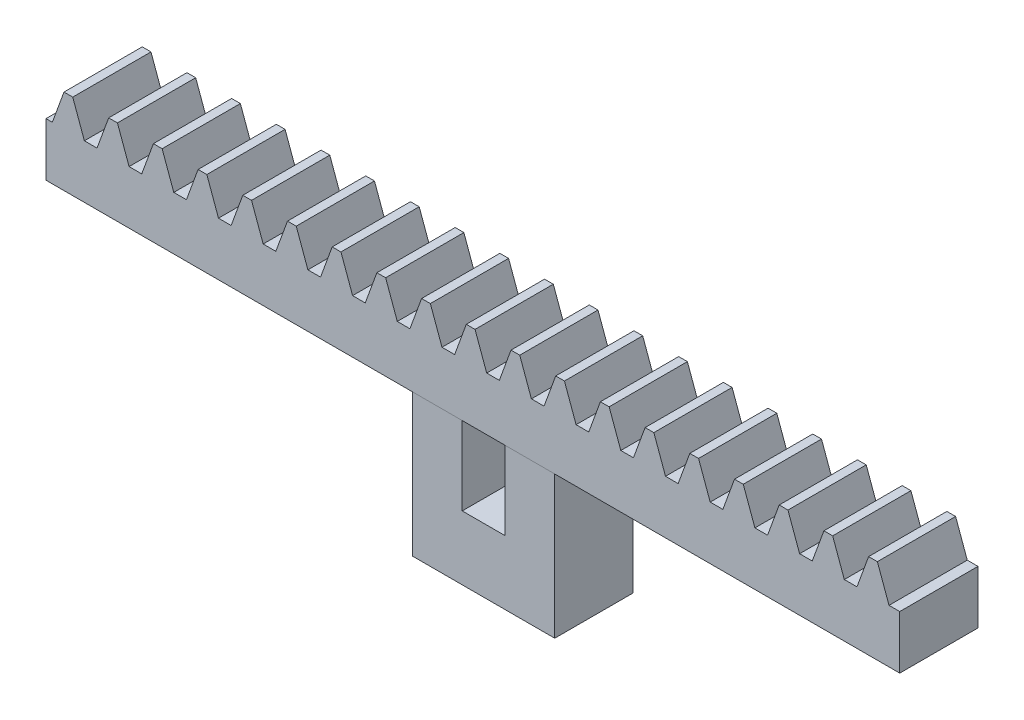
SolidWorks part; units mm, degrees
extrude "Blank" add sketch "BlankSke" against normal blind 5.5
sketch "BlankSke" plane through (0, 0, 0) normal (0, 0, 1) x (1, 0, 0)
  line L1 (0, 0) -> (60, 0)
  line L2 (0, 0) -> (0, 6)
  line L3 (0, 6) -> (60, 6)
  line L4 (60, 0) -> (60, 6)
  dimension "Length" = 60
  dimension "Blank_height" = 6
ref_plane "Plane1" through (0, 0, 0) normal (0, 0, 1) x (1, 0, 0)
ref_plane "Plane2" through (0, 0, 0) normal (0, 1, 0) x (1, 0, 0)
ref_plane "Plane3" through (0, 0, 0) normal (1, 0, 0) x (0, 0, -1)
sketch "HoldingSke" plane through (0, 0, 0) normal (0, 1, 0) x (1, 0, 0)
  line L0 (0, 0) -> (0.1392, 0.9903)
  line L1 (-15, 0) -> (100, 0) construction
  line L2 (0, 0) -> (-2.1039, 2.3779)
  line L3 (0, 0) -> (-11.863, 4.5341)
  line L4 (0, 0) -> (8.0624, 3.0949)
  line L5 (0, 0) -> (-23.7986, -8.8762)
  line L6 (0, 0) -> (-10.5278, -7.1032)
  line L9 (-71.009, 38.7566) -> (-14.6274, 59.2778)
  line L10 (-76.2, 3.3779) -> (-71.2, 3.3779)
  line L11 (0, 0) -> (-5.5, 0)
  line L12 (-76.2, 101.6) -> (-76.162, 101.6)
  line L13 (24.9733, 27.94) -> (52.9518, 28.4284)
  line L14 (24.9733, 27.94) -> (24.9743, 27.94)
  line L15 (24.9733, 27.94) -> (100.4006, 29.5858)
  circle A0 centre (0, 0) radius 19.05
  circle A1 centre (0, 0) radius 2.5
  circle A2 centre (0, 0) radius 12.7
  dimension "MPH" = 5
  dimension "Diameter" = 38.1
  dimension "Num_teeth" = 21
  dimension "Pitch" = 1
  dimension "Show_teeth" = 998
  dimension "Thickness" = 12.7
  dimension "Ap" = 20
  dimension "Pitch_height" = 5
  dimension "Width" = 5.5
  dimension "Backlash" = 0.038
  dimension "Addendum_fac" = 1
  dimension "Dedendum_fac" = 1.25
  dimension "Clearance_fac" = 0.25
  dimension "Dedendum_add" = 0.001
  dimension "Length" = 60
  dimension "Module" = 1
sketch "TooCutSkeIll" plane through (0, 0, 0) normal (0, 0, 1) x (1, 0, 0)
  line L0 (-1.2538, 5.9737) -> (-0.5045, 3.9152)
  line L1 (-0.2687, 3.75) -> (0.2687, 3.75)
  line L2 (0.5045, 3.9152) -> (1.2538, 5.9737)
  line L3 (60, 6) -> (0, 6) construction
  line L4 (0, 0) -> (0, 64.897) construction
  line L5 (-13.208, 5) -> (12.954, 5) construction
  line L6 (0, 0) -> (60, 0) construction
  line L7 (0.8994, 5) -> (0.8994, 48.7463) construction
  line L8 (-0.8994, 5) -> (-0.8994, 48.7463) construction
  line L9 (1.2914, 6) -> (1.2914, 6.0254)
  line L10 (-1.2914, 6) -> (-1.2914, 6.0254)
  line L11 (-1.2914, 6.0254) -> (1.2914, 6.0254)
  arc A0 (0.2687, 3.75) -> (0.5045, 3.9152) centre (0.2687, 4.001) ccw
  arc A1 (-0.5045, 3.9152) -> (-0.2687, 3.75) centre (-0.2687, 4.001) ccw
  arc A2 (1.2914, 6) -> (1.2538, 5.9737) centre (1.2914, 5.96) ccw
  arc A3 (-1.2538, 5.9737) -> (-1.2914, 6) centre (-1.2914, 5.96) ccw
  dimension "Pitch_height" = 5
  dimension "Addendum_plus" = 1.0254
  dimension "Pressure_angle" = 20
  dimension "Gap_width" = 1.7988
  dimension "Dedendum" = 1.25
extrude "ToothCutIll" [suppressed] cut sketch "TooCutSkeIll" against normal through all
sketch "TooCutSkeSim" plane through (0, 0, 0) normal (0, 0, 1) x (1, 0, 0)
  line L0 (0.4444, 3.75) -> (-0.4444, 3.75)
  line L1 (1.2726, 6.0254) -> (0.4444, 3.75)
  line L2 (0, 17.4625) -> (0, 53.467) construction
  line L3 (1.2726, 6.0254) -> (-1.2726, 6.0254)
  line L6 (-1.2726, 6.0254) -> (-0.4444, 3.75)
  line L9 (-0.8994, 5) -> (0.8994, 5) construction
  line L10 (0, 0) -> (60, 0) construction
  line L11 (0.8994, 5) -> (0.8994, 53.467) construction
  line L12 (-0.8994, 5) -> (-0.8994, 53.467) construction
  dimension "Pitch_height" = 5
  dimension "Addendum_plus" = 1.0254
  dimension "Pressure_angle" = 20
  dimension "Gap_width" = 1.7988
  dimension "Dedendum" = 1.25
extrude "ToothCutSim" cut sketch "TooCutSkeSim" against normal through all
pattern_linear "TeethCuts" count 20 spacing 3.1416 along (1, 0, 0) of "ToothCutIll", "ToothCutSim"
sketch "ｽｹｯﾁ1" plane through (0, 0, 0) normal (0, 0, 1) x (1, 0, 0)
  line L0 (0, 0) -> (60, 0) construction
  line L1 (35.7525, -10) -> (25.7525, -10)
  line L2 (35.7525, -10) -> (35.7525, 0)
  line L3 (35.7525, 0) -> (25.7525, 0)
  line L4 (25.7525, -10) -> (25.7525, 0)
  line L5 (35.7525, -10) -> (25.7525, 0) construction
  line L6 (35.7525, 0) -> (25.7525, -10) construction
  point P0 (30.7525, -5)
  dimension "D1" = 10
  dimension "D2" = 10
extrude "ﾎﾞｽ - 押し出し1" add sketch "ｽｹｯﾁ1" against normal blind 5.5 separate body
sketch "ｽｹｯﾁ2" plane through (0, 0, 0) normal (0, 0, 1) x (1, 0, 0)
  line L0 (35.7525, 0) -> (25.7525, 0) construction
  line L1 (32.2525, 0) -> (29.2525, 0)
  line L2 (32.2525, 0) -> (32.2525, -5.5)
  line L3 (32.2525, -5.5) -> (29.2525, -5.5)
  line L4 (29.2525, 0) -> (29.2525, -5.5)
  line L5 (32.2525, 0) -> (29.2525, -5.5) construction
  line L6 (32.2525, -5.5) -> (29.2525, 0) construction
  line L8 (35.7525, -10) -> (35.7525, 0) construction
  point P0 (30.7525, -2.75)
  dimension "D1" = 3
  dimension "D2" = 5.5
  dimension "D3" = 5
extrude "ｶｯﾄ - 押し出し1" cut sketch "ｽｹｯﾁ2" against normal through all
equation "' \"Module@HoldingSke\" = 6.35"
equation "' \"Num_teeth@HoldingSke\" = 12"
equation "' \"Ap@HoldingSke\" =  20"
equation "' \"Ap@HoldingSke\" = 20"
equation "' \"Width@HoldingSke\" = 0.25 * 25.4"
equation "' \"Show_teeth@HoldingSke\" = 500"
equation "' \"Backlash@HoldingSke\" = 0.009 * 25.4"
equation "' \"Addendum_fac@HoldingSke\" = 1.0"
equation "' \"Dedendum_fac@HoldingSke\" = 1.25"
equation "' \"Dedendum_add@HoldingSke\" = 0.00005 * 25.4"
equation "' \"Clearance_fac@HoldingSke\" = 0.25"
equation "' \"Pitch_height@HoldingSke\" = 1 * 25.4"
equation "' \"Length@HoldingSke\" = 4.71 * 25.4"
equation "\"Pitch@HoldingSke\" = 1 / \"Module@HoldingSke\""
equation "\"MPH@HoldingSke\" = \"Dedendum_fac@HoldingSke\" / \"Pitch@HoldingSke\" + 2 * \"Dedendum_add@HoldingSke\" + 0.002 * 25.4"
equation "\"MPH@HoldingSke\" = ((sgn( \"MPH@HoldingSke\" - \"Pitch_height@HoldingSke\")+1)*( \"MPH@HoldingSke\" - \"Pitch_height@HoldingSke\"))/2 + \"Pitch_height@HoldingSke\""
equation "\"Blank_height@BlankSke\" = \"Pitch_height@HoldingSke\" + \"Addendum_fac@HoldingSke\"  / \"Pitch@HoldingSke\" "
equation "\"Length@BlankSke\" =  \"Length@HoldingSke\""
equation "\"Face_width@Blank\" = \"Width@HoldingSke\""
equation "\"Pressure_angle@TooCutSkeIll\" = \"Ap@HoldingSke\""
equation "\"Addendum_plus@TooCutSkeIll\" =  \"Addendum_fac@HoldingSke\"  / \"Pitch@HoldingSke\" + 0.001 *25.4"
equation "\"Dedendum@TooCutSkeIll\" = \"Dedendum_fac@HoldingSke\"  / \"Pitch@HoldingSke\""
equation "\"Pitch_height@TooCutSkeIll\" =  \"MPH@HoldingSke\""
equation "\"Gap_width@TooCutSkeIll\" = 3.14159265 / 2 / \"Pitch@HoldingSke\" + 6 * \"Backlash@HoldingSke\""
equation "\"Pressure_angle@TooCutSkeSim\" = \"Ap@HoldingSke\""
equation "\"Addendum_plus@TooCutSkeSim\" =  \"Addendum_fac@HoldingSke\"  / \"Pitch@HoldingSke\" + 0.001 * 25.4"
equation "\"Dedendum@TooCutSkeSim\" = \"Dedendum_fac@HoldingSke\"  / \"Pitch@HoldingSke\""
equation "\"Pitch_height@TooCutSkeSim\" =  \"MPH@HoldingSke\""
equation "\"Gap_width@TooCutSkeSim\" = 3.14159265 / 2 / \"Pitch@HoldingSke\" + 6 * \"Backlash@HoldingSke\""
equation "\"Root_fillet@TooCutSkeIll\" = \"Clearance_fac@HoldingSke\" / \"Pitch@HoldingSke\" + \"Dedendum_add@HoldingSke\""
equation "\"Break_rad@TooCutSkeIll\" = 0.02 / \"Pitch@HoldingSke\" * 2"
equation "\"Linear_pitch@TeethCuts\" = 3.14159265 / \"Pitch@HoldingSke\""
equation "\"Num_teeth@HoldingSke\" = int( ( \"Length@HoldingSke\" + 0 ) / (3.14159265 / \"Pitch@HoldingSke\")) + 0.9999  + 1"
equation " \"Num_teeth@TeethCuts\" = int( \"Show_teeth@HoldingSke\" ) + 1"
equation " \"Num_teeth@TeethCuts\" = ((sgn( \"Num_teeth@TeethCuts\" - \"Num_teeth@HoldingSke\" )-1)*( \"Num_teeth@TeethCuts\" - \"Num_teeth@HoldingSke\" ))/-2+ \"Num_teeth@HoldingSke\""
equation " \"Num_teeth@TeethCuts\" = ((sgn( \"Num_teeth@TeethCuts\" - 2.0)+1)*( \"Num_teeth@TeethCuts\" - 2.0))/2 +2.0"
